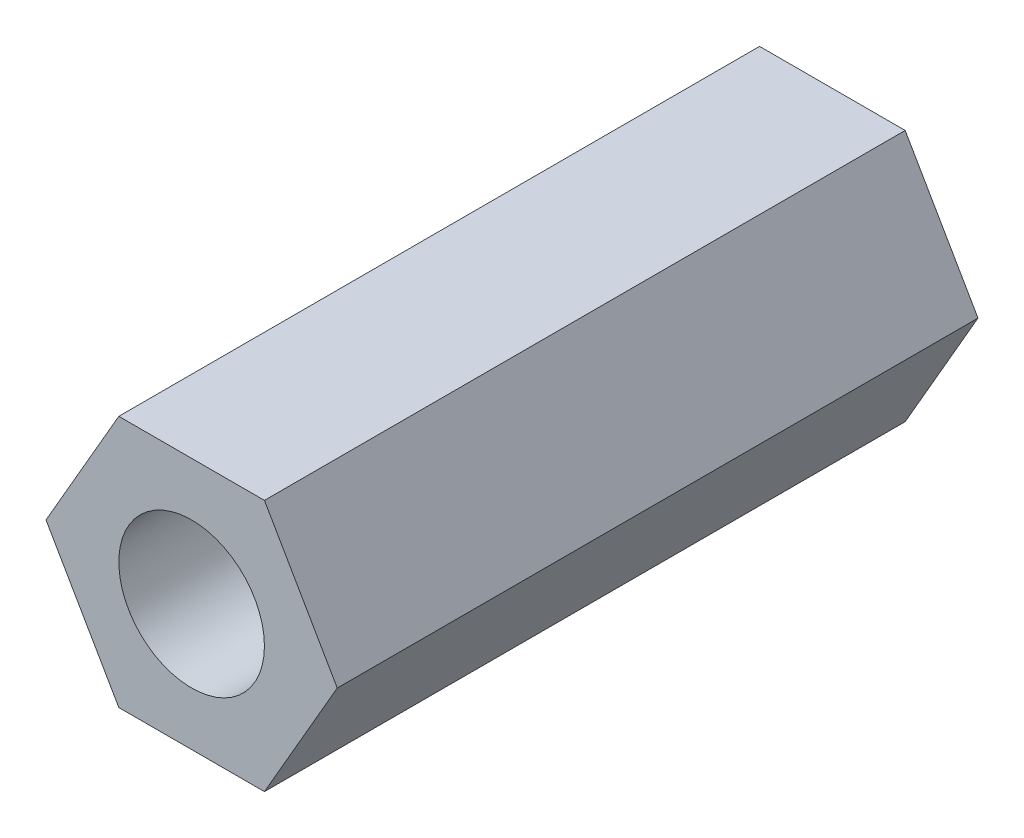
SolidWorks part; units mm, degrees
material "普通碳钢"
ref_plane "前视" through (0, 0, 0) normal (0, 0, 1) x (1, 0, 0)
ref_plane "上视" through (0, 0, 0) normal (0, 1, 0) x (1, 0, 0)
ref_plane "右视" through (0, 0, 0) normal (1, 0, 0) x (0, 0, -1)
sketch "草图1" plane through (0, 0, 0) normal (0, 0, 1) x (1, 0, 0)
  line L0 (0, 0) -> (2.5, 0)
  line L1 (2.5, 0) -> (3.75, -2.1651)
  line L2 (3.75, -2.1651) -> (2.5, -4.3301)
  line L3 (2.5, -4.3301) -> (0, -4.3301)
  line L4 (0, -4.3301) -> (-1.25, -2.1651)
  line L5 (-1.25, -2.1651) -> (0, 0)
  dimension "D1" = 5
  dimension "D2" = 5
extrude "凸台-拉伸1" add sketch "草图1" along normal blind 11
hole_wizard "M3 螺纹孔1" positions "草图3" profile "草图2" tap size "M3" standard "GB" end condition through all
sketch "草图3" plane through (0, 0, 11) normal (0, 0, 1) x (1, 0, 0)
  line L0 (-1.25, -2.1651) -> (3.75, -2.1651) construction
  line L2 (1.25, 0) -> (1.25, -4.3301) construction
  line L3 (2.5, 0) -> (0, 0) construction
  line L4 (0, -4.3301) -> (2.5, -4.3301) construction
  point P0 (1.25, -2.1651)
cosmetic thread "孔螺蚊线1" parameters "D2"=3
sketch "草图2" plane through (1.25, -2.1651, 11) normal (1, 0, 0) x (0, -1, 0)
  line L0 (0, 0) -> (0, 11)
  line L1 (0, 11) -> (1.25, 11)
  line L2 (1.25, 11) -> (1.25, 0)
  line L5 (1.25, 0) -> (0, 0)
  line L11 (0, -6.35) -> (0, 107.95) construction
  dimension "通孔螺纹孔钻头直径" = 2.5
  dimension "通孔螺纹孔钻头深度" = 11
